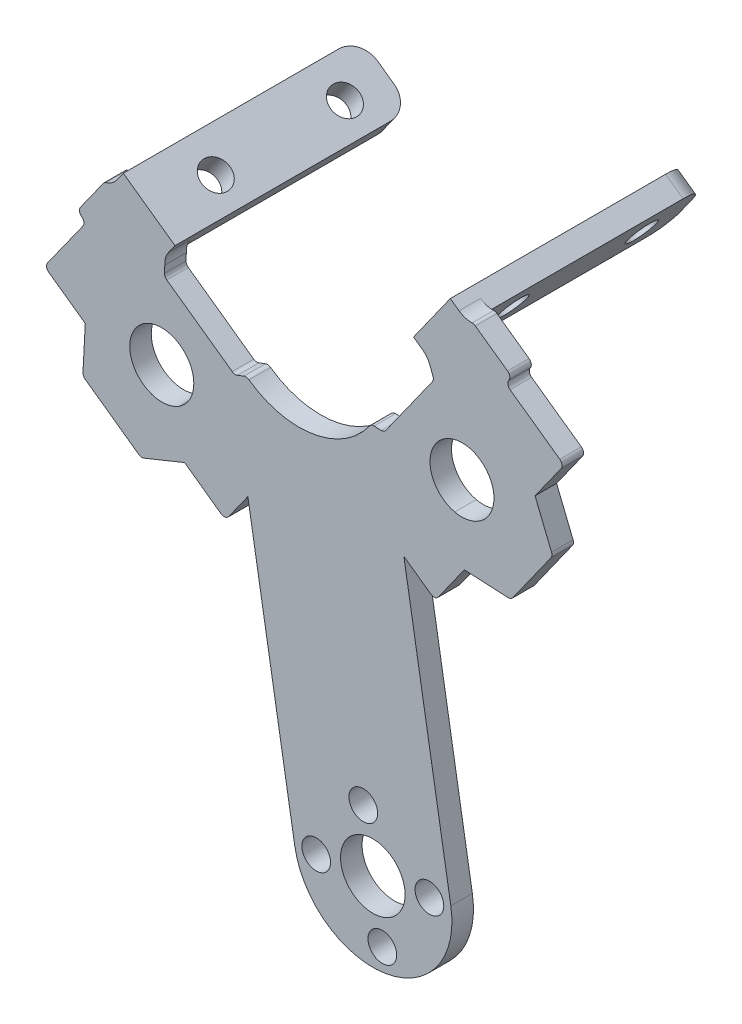
SolidWorks part; units mm, degrees
ref_plane "前视基准面" through (0, 0, 0) normal (0, 0, 1) x (1, 0, 0)
ref_plane "上视基准面" through (0, 0, 0) normal (0, 1, 0) x (1, 0, 0)
ref_plane "右视基准面" through (0, 0, 0) normal (1, 0, 0) x (0, 0, -1)
sketch "草图2" plane through (0, 0, 0) normal (0, 0, 1) x (1, 0, 0)
  circle A0 centre (0, 0) radius 73.8991
extrude "凸台-拉伸2" add sketch "草图2" along normal blind 3
sketch "草图6" plane through (0, 0, 3) normal (0, 0, 1) x (1, 0, 0)
  line L0 (-31.535, 35.3929) -> (-24.3307, 30.2552)
  line L1 (-24.0166, 29.6209) -> (-24.0481, 28.6214)
  line L2 (-23.7339, 27.9872) -> (-14.6174, 21.4858)
  line L3 (-13.9155, 21.3954) -> (-12.9807, 21.7507)
  line L6 (-15.1202, 3.7278) -> (-12.4398, 7.4864)
  line L7 (-16.1663, 3.5526) -> (-21.2549, 7.1815)
  line L8 (-21.2549, 7.1815) -> (-26.9163, 4.8902)
  line L9 (-35.1045, 10.303) -> (-27.6331, 4.9748)
  line L10 (-35.0958, 17.0522) -> (-35.4179, 10.9532)
  line L11 (-40.1844, 20.6811) -> (-35.0958, 17.0522)
  line L12 (-35.4242, 28.6476) -> (-40.3595, 21.7272)
  line L13 (-32.5811, 35.2177) -> (-35.7745, 30.7398)
  line L14 (4.9781, -29.5979) -> (0, 0) construction
  line L15 (19.2678, 43.9382) -> (23.7504, 40.7513)
  line L16 (24.1038, 38.6597) -> (31.0314, 33.7344)
  line L17 (31.2081, 32.6886) -> (27.5866, 27.5947)
  line L18 (27.5866, 27.5947) -> (29.8862, 21.9367)
  line L19 (29.8026, 21.2197) -> (24.4854, 13.7407)
  line L20 (17.7362, 13.7395) -> (23.8357, 13.4262)
  line L21 (14.1147, 8.6456) -> (17.7362, 13.7395)
  line L22 (13.0689, 8.4689) -> (9.3063, 11.1439)
  line L25 (6.1508, 24.7703) -> (5.1513, 24.8004)
  line L26 (13.2727, 34.2113) -> (6.7846, 25.0854)
  line L27 (13.0054, 35.8477) -> (13.3621, 34.9135)
  line L28 (18.222, 43.7616) -> (13.0948, 36.5498)
  line L29 (15.8511, -27.7692) -> (9.3063, 11.1439)
  line L30 (-5.895, -31.4266) -> (-12.4398, 7.4864)
  arc A0 (-5.895, -31.4266) -> (15.8511, -27.7692) centre (4.9781, -29.5979) ccw
  arc A1 (-32.5811, 35.2177) -> (-31.535, 35.3929) centre (-31.9705, 34.7823) cw
  arc A2 (-35.7745, 30.7398) -> (-35.5994, 29.6937) centre (-35.1639, 30.3043) ccw
  arc A3 (-35.4242, 28.6476) -> (-35.5994, 29.6937) centre (-36.0349, 29.0831) ccw
  arc A4 (-40.3595, 21.7272) -> (-40.1844, 20.6811) centre (-39.7489, 21.2917) ccw
  arc A5 (-24.3307, 30.2552) -> (-24.0166, 29.6209) centre (-24.7662, 29.6446) cw
  arc A6 (-24.0481, 28.6214) -> (-23.7339, 27.9872) centre (-23.2984, 28.5978) ccw
  arc A7 (-14.6174, 21.4858) -> (-13.9155, 21.3954) centre (-14.182, 22.0964) ccw
  arc A8 (-12.9807, 21.7507) -> (-12.2787, 21.6603) centre (-12.7142, 21.0497) cw
  arc A12 (-15.1202, 3.7278) -> (-16.1663, 3.5526) centre (-15.7309, 4.1632) cw
  arc A13 (-26.9163, 4.8902) -> (-27.6331, 4.9748) centre (-27.1977, 5.5855) cw
  arc A14 (-35.1045, 10.303) -> (-35.4179, 10.9532) centre (-34.669, 10.9136) cw
  arc A15 (29.8026, 21.2197) -> (29.8862, 21.9367) centre (29.1914, 21.6543) ccw
  arc A16 (23.8357, 13.4262) -> (24.4854, 13.7407) centre (23.8741, 14.1752) ccw
  arc A17 (13.0689, 8.4689) -> (14.1147, 8.6456) centre (13.5035, 9.0802) ccw
  arc A21 (5.1513, 24.8004) -> (4.5175, 24.4853) centre (5.1288, 24.0507) ccw
  arc A22 (6.7846, 25.0854) -> (6.1508, 24.7703) centre (6.1734, 25.52) cw
  arc A23 (13.3621, 34.9135) -> (13.2727, 34.2113) centre (12.6614, 34.6459) cw
  arc A24 (13.0948, 36.5498) -> (13.0054, 35.8477) centre (13.706, 36.1152) ccw
  arc A25 (31.0314, 33.7344) -> (31.2081, 32.6886) centre (30.5969, 33.1232) cw
  arc A26 (24.1038, 38.6597) -> (23.9271, 39.7055) centre (24.5384, 39.2709) cw
  arc A27 (23.7504, 40.7513) -> (23.9271, 39.7055) centre (23.3158, 40.1401) cw
  arc A28 (19.2678, 43.9382) -> (18.222, 43.7616) centre (18.8333, 43.327) ccw
  arc A29 (-12.2787, 21.6603) -> (4.5175, 24.4853) centre (-5.291, 31.4587) ccw
extrude "切除-拉伸4" cut sketch "草图6" against normal blind 10 flip side to cut
sketch "草图7" plane through (0, 0, 3) normal (0, 0, 1) x (1, 0, 0)
  line L0 (6.8068, -40.471) -> (3.6512, -21.7087) construction
  line L1 (-5.895, -31.4266) -> (15.8511, -27.7692) construction
  circle A0 centre (4.9781, -29.5979) radius 4.5
  circle A1 centre (4.9781, -29.5979) radius 8 construction
  arc A2 (-5.895, -31.4266) -> (15.8511, -27.7692) centre (4.9781, -29.5979) ccw construction
  circle A3 centre (3.6512, -21.7087) radius 2
  circle A4 centre (12.8673, -28.271) radius 2
  circle A5 centre (6.305, -37.4871) radius 2
  circle A6 centre (-2.9111, -30.9248) radius 2
  dimension "D1" = 9
  dimension "D2" = 16
  dimension "D3" = 4
  dimension "D4" = 4
  dimension "D5" = 4
  dimension "D6" = 4
extrude "切除-拉伸5" cut sketch "草图7" against normal blind 10
sketch "草图8" plane through (0, 0, 3) normal (0, 0, 1) x (1, 0, 0)
  circle A0 centre (-24.4013, 17.409) radius 4.5
  circle A1 centre (17.4426, 24.4153) radius 4.5
extrude "切除-拉伸6" cut sketch "草图8" against normal blind 10
sketch "草图9" plane through (-3.7707, -5.2873, 0) normal (-0.5806, -0.8142, 0) x (0.8142, -0.5806, 0)
  line L0 (-29.9749, 3) -> (-29.9749, -30) construction
  line L5 (-34.5632, 3) -> (-25.3866, 3) construction
  line L6 (-38.4749, -30) -> (-44.7249, -30)
  line L7 (-44.7249, 3) -> (-44.7249, -30)
  line L8 (-38.4749, 3) -> (-44.7249, 3)
  line L9 (-38.4749, 3) -> (-38.4749, -30)
  circle A2 centre (-41.4528, -24) radius 2
  circle A3 centre (-41.4528, -6) radius 2
ref_plane "基准面4" through (0, 0, 0) normal (-0.9861, -0.1659, 0) x (0, 0, 1)
mirror "镜向3" about plane through (0, 0, 0) normal (-0.9861, -0.1659, 0) of bodies 110 111
extrude "凸台-拉伸3" add sketch "草图9" against normal blind 20
sketch "草图10" plane through (-3.7707, -5.2873, 0) normal (-0.5806, -0.8142, 0) x (0.8142, -0.5806, 0)
  line L1 (-38.4749, -30) -> (-44.7249, -30)
  line L2 (-38.4749, -30) -> (-38.4749, 0)
  line L3 (-38.4749, 0) -> (-44.7249, 0)
  line L4 (-44.7249, -30) -> (-44.7249, 0)
extrude "切除-拉伸7" cut sketch "草图10" against normal blind 17 contours L2 L1 L4 L3
sketch "草图11" plane through (6.1, 8.5536, 0) normal (0.5806, 0.8142, 0) x (0.8142, -0.5806, 0)
  line L1 (-44.7249, -3) -> (-46.2249, -3)
  line L2 (-44.7249, -3) -> (-44.7249, 30)
  line L3 (-44.7249, 30) -> (-46.2249, 30)
  line L4 (-46.2249, -3) -> (-46.2249, 30)
  line L5 (-38.4749, -3) -> (-37.3763, -3)
  line L6 (-38.4749, -3) -> (-38.4749, 30)
  line L7 (-38.4749, 30) -> (-37.3763, 30)
  line L8 (-37.3763, -3) -> (-37.3763, 30)
  dimension "D1" = 1.5
  dimension "D2" = 33
  dimension "D3" = 1.0986
  dimension "D4" = 33
extrude "凸台-拉伸4" add sketch "草图11" along normal up to vertex (3 mm away) up to point (-23.4833, 33.3356, 3)
fillet "圆角1" radius 3 4 edges at (-31.535, 35.3929, 1.5) (-24.3307, 30.2552, 1.5) (-23.4598, 31.4764, -30) (-30.6641, 36.6142, -30)
mirror "镜向4" about plane through (0, 0, 0) normal (-0.9861, -0.1659, 0) of bodies 121
